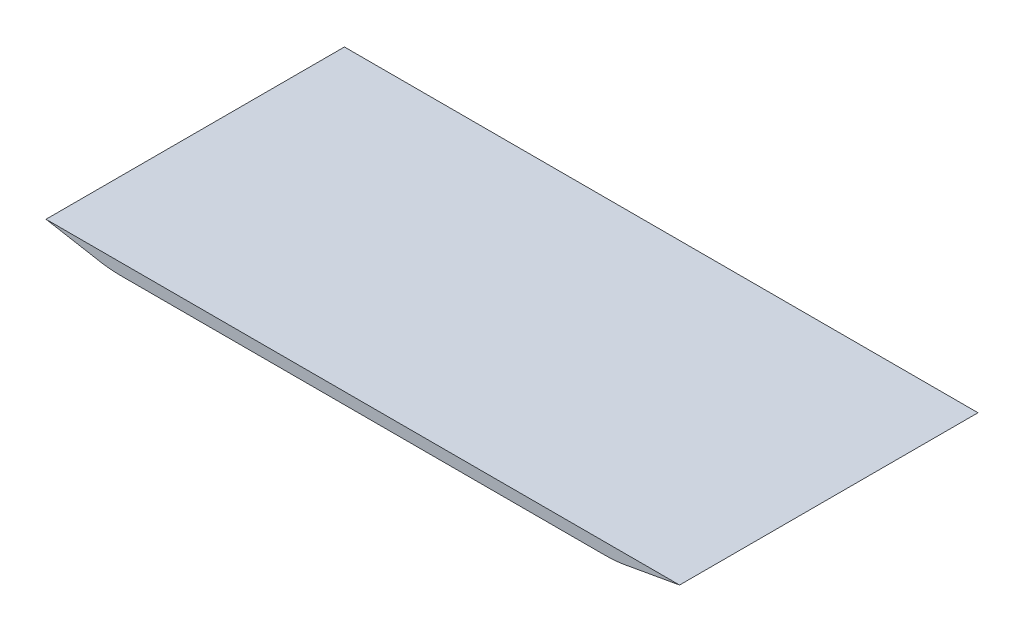
SolidWorks part; units mm, degrees
ref_plane "Front Plane" through (0, 0, 0) normal (0, 0, 1) x (1, 0, 0)
ref_plane "Top Plane" through (0, 0, 0) normal (0, 1, 0) x (1, 0, 0)
ref_plane "Right Plane" through (0, 0, 0) normal (1, 0, 0) x (0, 0, -1)
sketch "Sketch1" plane through (0, 0, 0) normal (0, 0, 1) x (1, 0, 0)
  line L0 (0, 0) -> (276, 0)
  line L2 (248, -5) -> (28, -5)
  line L3 (28, -5) -> (0, 0)
  line L4 (276, 0) -> (248, -5)
  dimension "D1" = 5
  dimension "D2" = 28
  dimension "D3" = 28
  dimension "D4" = 220
extrude "Boss-Extrude1" add sketch "Sketch1" along normal blind 130 contours L3 L0 L4 L2
fillet "Fillet1" radius 50 2 edges at (248, -5, 65) (28, -5, 65)
